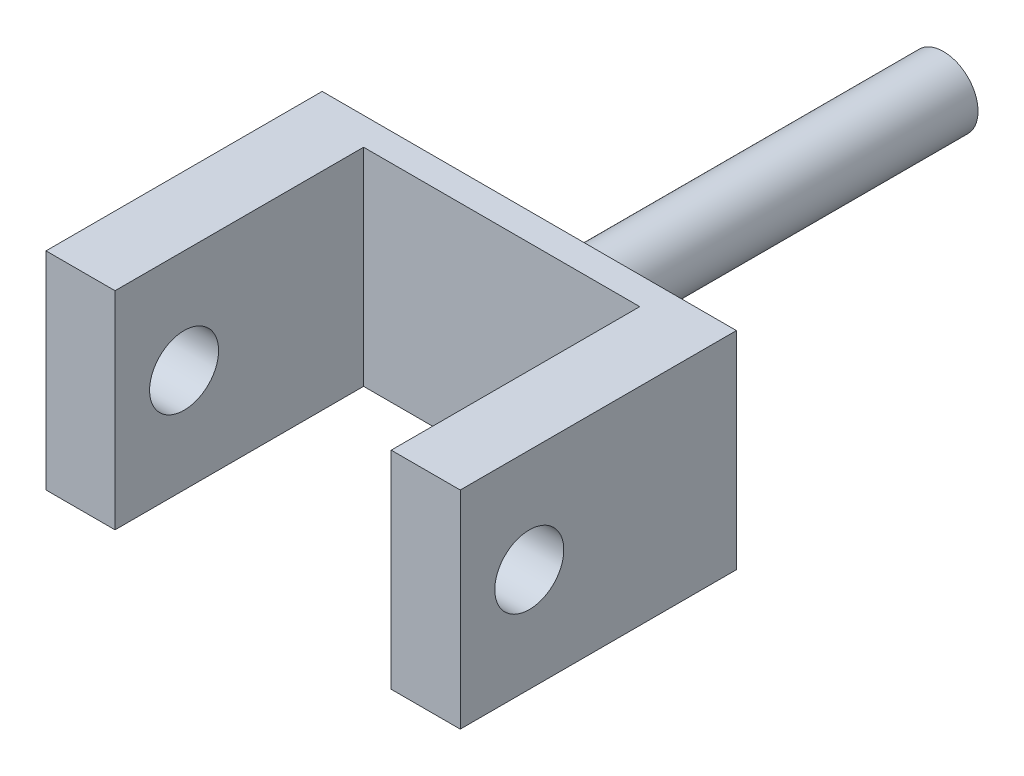
SolidWorks part; units mm, degrees
ref_plane "정면" through (0, 0, 0) normal (0, 0, 1) x (1, 0, 0)
ref_plane "윗면" through (0, 0, 0) normal (0, 1, 0) x (1, 0, 0)
ref_plane "우측면" through (0, 0, 0) normal (1, 0, 0) x (0, 0, -1)
sketch "스케치1" plane through (0, 0, 0) normal (0, 1, 0) x (1, 0, 0)
  line L0 (-100, -100) -> (-150, -100)
  line L1 (150, -100) -> (100, -100)
  line L2 (150, -100) -> (150, 100)
  line L3 (150, 100) -> (-150, 100)
  line L4 (-150, -100) -> (-150, 100)
  line L5 (150, -100) -> (-150, 100) construction
  line L6 (150, 100) -> (-150, -100) construction
  line L8 (-100, -100) -> (-100, 80)
  line L9 (-100, 80) -> (100, 80)
  line L10 (100, -100) -> (100, 80)
  point P0 (0, 0)
  dimension "D1" = 300
  dimension "D2" = 200
  dimension "D3" = 50
  dimension "D4" = 50
  dimension "D5" = 20
extrude "보스-돌출1" add sketch "스케치1" along normal blind 150
sketch "스케치2" plane through (0, 0, -100) normal (0, 0, -1) x (-1, 0, 0)
  line L0 (150, 150) -> (150, 0) construction
  circle A0 centre (0, 75) radius 25
  point P6 (150, 75)
  dimension "D1" = 50
extrude "보스-돌출2" add sketch "스케치2" along normal blind 300
sketch "스케치3" plane through (-150, 0, 0) normal (-1, 0, 0) x (0, 0, 1)
  line L0 (100, 150) -> (100, 0) construction
  circle A0 centre (50, 75) radius 25
  point P7 (100, 75)
  dimension "D1" = 50
  dimension "D2" = 50
extrude "컷-돌출1" cut sketch "스케치3" against normal blind 300
